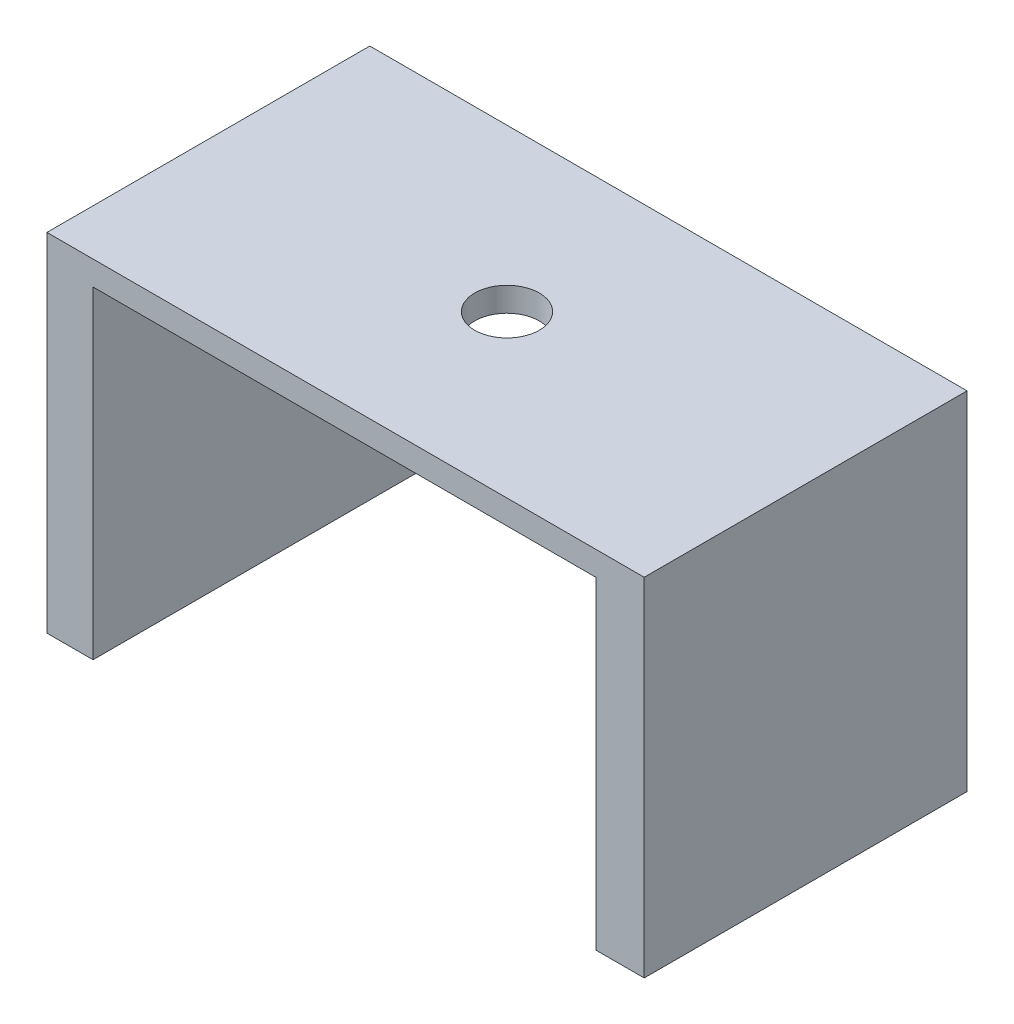
SolidWorks part; units mm, degrees
ref_plane "Front Plane" through (0, 0, 0) normal (0, 0, 1) x (1, 0, 0)
ref_plane "Top Plane" through (0, 0, 0) normal (0, 1, 0) x (1, 0, 0)
ref_plane "Right Plane" through (0, 0, 0) normal (1, 0, 0) x (0, 0, -1)
sketch "Sketch1" plane through (0, 0, 0) normal (0, 1, 0) x (1, 0, 0)
  line L1 (-185, 100) -> (185, 100)
  line L2 (-185, 100) -> (-185, -100)
  line L3 (-185, -100) -> (185, -100)
  line L4 (185, 100) -> (185, -100)
  line L5 (-185, 100) -> (185, -100) construction
  line L6 (-185, -100) -> (185, 100) construction
  point P1 (0, 0)
  dimension "D1" = 370
  dimension "D2" = 200
extrude "Boss-Extrude1" add sketch "Sketch1" along normal blind 15
sketch "Sketch2" plane through (0, 0, 0) normal (0, -1, 0) x (1, 0, 0)
  line L0 (185, -100) -> (-185, -100) construction
  line L1 (-185, 100) -> (-156.4383, 100)
  line L2 (-185, 100) -> (-185, -100)
  line L3 (-185, -100) -> (-156.4383, -100)
  line L4 (-156.4383, 100) -> (-156.4383, -100)
  line L6 (185, 100) -> (155, 100)
  line L7 (185, 100) -> (185, -100)
  line L8 (185, -100) -> (155, -100)
  line L9 (155, 100) -> (155, -100)
  dimension "D1" = 30
  dimension "30" = 28.5617
extrude "Boss-Extrude2" add sketch "Sketch2" along normal blind 200
sketch "Sketch3" plane through (0, 15, 0) normal (0, 1, 0) x (1, 0, 0)
  circle A0 centre (0, 0) radius 20
  dimension "D1" = 40
extrude "Cut-Extrude1" cut sketch "Sketch3" against normal blind 200 contours A0
